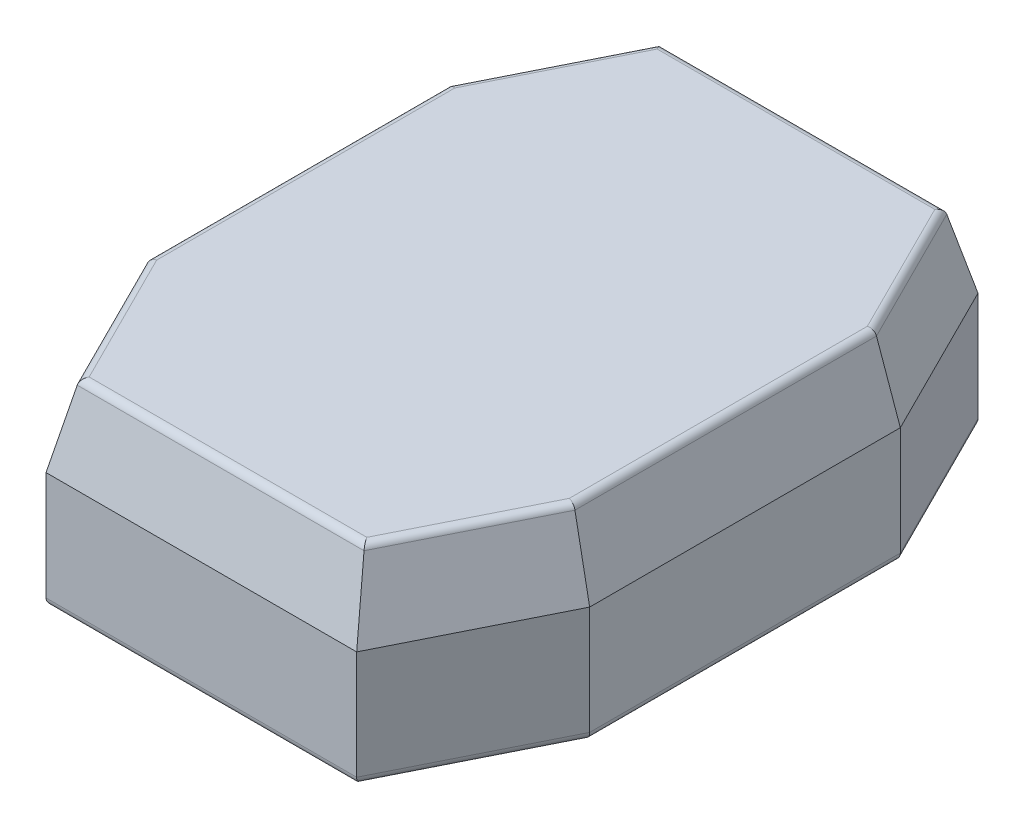
SolidWorks part; units mm, degrees
ref_plane "Front Plane" through (0, 0, 0) normal (0, 0, 1) x (1, 0, 0)
ref_plane "Top Plane" through (0, 0, 0) normal (0, 1, 0) x (1, 0, 0)
ref_plane "Right Plane" through (0, 0, 0) normal (1, 0, 0) x (0, 0, -1)
sketch "Sketch1" plane through (0, 0, 0) normal (0, 1, 0) x (1, 0, 0)
  line L0 (-7.62, 5.08) -> (-5.08, 10.16)
  line L1 (-5.08, 10.16) -> (5.08, 10.16)
  line L2 (-7.62, 5.08) -> (-7.62, -5.08)
  line L3 (-5.08, -10.16) -> (5.08, -10.16)
  line L4 (7.62, 5.08) -> (7.62, -5.08)
  line L5 (-7.62, 10.16) -> (7.62, -10.16) construction
  line L6 (-7.62, -10.16) -> (7.62, 10.16) construction
  line L7 (5.08, 10.16) -> (7.62, 5.08)
  line L8 (5.08, -10.16) -> (7.62, -5.08)
  line L9 (-7.62, -5.08) -> (-5.08, -10.16)
  point P0 (0, 0)
  dimension "D1" = 15.24
  dimension "D2" = 20.32
  dimension "D3" = 2.54
  dimension "D4" = 5.08
  dimension "D5" = 2.54
  dimension "D6" = 5.08
  dimension "D7" = 2.54
  dimension "D8" = 5.08
  dimension "D9" = 5.08
  dimension "D10" = 2.54
extrude "Boss-Extrude1" add sketch "Sketch1" along normal blind 2.54 draft 15
sketch "Stem" plane through (0, 0, 0) normal (0, -1, 0) x (1, 0, 0)
  line L1 (-0.5625, 2.075) -> (0.5625, 2.075)
  line L2 (-0.5625, 2.075) -> (-0.5625, -2.075)
  line L3 (-0.5625, -2.075) -> (0.5625, -2.075)
  line L4 (0.5625, 2.075) -> (0.5625, -2.075)
  line L5 (-0.5625, 2.075) -> (0.5625, -2.075) construction
  line L6 (-0.5625, -2.075) -> (0.5625, 2.075) construction
  line L7 (2.0625, 0.6625) -> (-2.0625, 0.6625)
  line L8 (2.0625, 0.6625) -> (2.0625, -0.6625)
  line L9 (2.0625, -0.6625) -> (-2.0625, -0.6625)
  line L10 (-2.0625, 0.6625) -> (-2.0625, -0.6625)
  line L11 (2.0625, 0.6625) -> (-2.0625, -0.6625) construction
  line L12 (2.0625, -0.6625) -> (-2.0625, 0.6625) construction
  line L13 (-2.5, 2.5) -> (2.5, 2.5)
  line L14 (-3, 2) -> (-3, -2)
  line L15 (-2.5, -2.5) -> (2.5, -2.5)
  line L16 (3, 2) -> (3, -2)
  line L17 (-3, 2.5) -> (3, -2.5) construction
  line L18 (-3, -2.5) -> (3, 2.5) construction
  arc A0 (-3, -2) -> (-2.5, -2.5) centre (-2.5, -2) ccw
  arc A1 (-2.5, 2.5) -> (-3, 2) centre (-2.5, 2) ccw
  arc A2 (2.5, -2.5) -> (3, -2) centre (2.5, -2) ccw
  arc A3 (2.5, 2.5) -> (3, 2) centre (2.5, 2) cw
  point P0 (0, 0)
  point P6 (0, 0)
  point P11 (0, 0)
  dimension "D7" = 0.5
  dimension "D1" = 4.15
  dimension "D2" = 1.125
  dimension "D3" = 1.325
  dimension "D4" = 4.125
  dimension "D5" = 5
  dimension "D6" = 6
extrude "Boss-Extrude2" add sketch "Stem" along normal blind 3.8 contours A3 L13 A1 L14 A0 L15 A2 L16 L10 L7 L2 L1 L4 L8 L9 L3
fillet "Fillet2" radius 0.1 8 edges at (-2.8536, -3.8, -2.3536) (-3, -3.8, 0) (-2.8536, -3.8, 2.3536) (0, -3.8, 2.5) (2.8536, -3.8, 2.3536) (3, -3.8, 0) (2.8536, -3.8, -2.3536) (0, -3.8, -2.5)
chamfer "Chamfer1" distance 0.2 angle 45 11 edges at (-0.5625, -3.8, -1.3688) (-1.3125, -3.8, -0.6625) (-2.0625, -3.8, 0) (0.5625, -3.8, -1.3688) (1.3125, -3.8, -0.6625) (2.0625, -3.8, 0) (1.3125, -3.8, 0.6625) (0.5625, -3.8, 1.3687) (0, -3.8, 2.075) (-0.5625, -3.8, 1.3687) (-1.3125, -3.8, 0.6625)
sketch "Sketch3" plane through (0, 0, 0) normal (0, -1, 0) x (1, 0, 0)
  line L0 (-7.62, 5.08) -> (-7.62, -5.08)
  line L1 (-7.62, -5.08) -> (-5.08, -10.16)
  line L2 (-5.08, -10.16) -> (5.08, -10.16)
  line L3 (5.08, -10.16) -> (7.62, -5.08)
  line L4 (7.62, -5.08) -> (7.62, 5.08)
  line L5 (7.62, 5.08) -> (5.08, 10.16)
  line L6 (5.08, 10.16) -> (-5.08, 10.16)
  line L7 (-5.08, 10.16) -> (-7.62, 5.08)
  line L44 (-6.35, -4.7802) -> (-4.2951, -8.89)
  line L45 (-4.2951, -8.89) -> (4.2951, -8.89)
  line L46 (4.2951, -8.89) -> (6.35, -4.7802)
  line L47 (6.35, -4.7802) -> (6.35, 4.7802)
  line L48 (6.35, 4.7802) -> (4.2951, 8.89)
  line L49 (4.2951, 8.89) -> (-4.2951, 8.89)
  line L50 (-4.2951, 8.89) -> (-6.35, 4.7802)
  line L51 (-6.35, 4.7802) -> (-6.35, -4.7802)
  line L52 (-6.35, -4.7802) -> (-4.2951, -8.89)
  line L53 (-4.2951, -8.89) -> (4.2951, -8.89)
  line L54 (4.2951, -8.89) -> (6.35, -4.7802)
  line L55 (6.35, -4.7802) -> (6.35, 4.7802)
  line L56 (6.35, 4.7802) -> (4.2951, 8.89)
  line L57 (4.2951, 8.89) -> (-4.2951, 8.89)
  line L58 (-4.2951, 8.89) -> (-6.35, 4.7802)
  line L59 (-6.35, 4.7802) -> (-6.35, -4.7802)
  dimension "D1" = 1.27
extrude "Boss-Extrude3" add sketch "Sketch3" along normal blind 3.8
fillet "Fillet3" radius 0.25 16 edges at (0, -3.8, -8.89) (5.3225, -3.8, -6.8351) (6.35, -3.8, 0) (5.3225, -3.8, 6.8351) (0, -3.8, 8.89) (-5.3225, -3.8, 6.8351) (-6.35, -3.8, 0) (-5.3225, -3.8, -6.8351) (0, -3.8, 10.16) (6.35, -3.8, 7.62) (7.62, -3.8, 0) (6.35, -3.8, -7.62) (0, -3.8, -10.16) (-6.35, -3.8, -7.62) (-7.62, -3.8, 0) (-6.35, -3.8, 7.62)
fillet "Fillet5" radius 0.5 16 edges at (0, 0, 2.5) (-2.8536, 0, 2.3536) (-3, 0, 0) (-2.8536, 0, -2.3536) (0, 0, -2.5) (2.8536, 0, -2.3536) (3, 0, 0) (2.8536, 0, 2.3536) (-5.3225, 0, 6.8351) (0, 0, 8.89) (5.3225, 0, 6.8351) (6.35, 0, 0) (5.3225, 0, -6.8351) (0, 0, -8.89) (-5.3225, 0, -6.8351) (-6.35, 0, 0)
fillet "Fillet6" radius 0.1 12 edges at (-1.3125, 0, 0.6625) (-0.5625, 0, 1.3687) (0, 0, 2.075) (0.5625, 0, 1.3687) (1.3125, 0, 0.6625) (2.0625, 0, 0) (1.3125, 0, -0.6625) (0.5625, 0, -1.3688) (0, 0, -2.075) (-0.5625, 0, -1.3688) (-1.3125, 0, -0.6625) (-2.0625, 0, 0)
fillet "Fillet7" radius 0.25 8 edges at (5.7994, 2.54, -7.1994) (6.9394, 2.54, 0) (5.7994, 2.54, 7.1994) (0, 2.54, 9.4794) (-5.7994, 2.54, 7.1994) (-6.9394, 2.54, 0) (-5.7994, 2.54, -7.1994) (0, 2.54, -9.4794)
